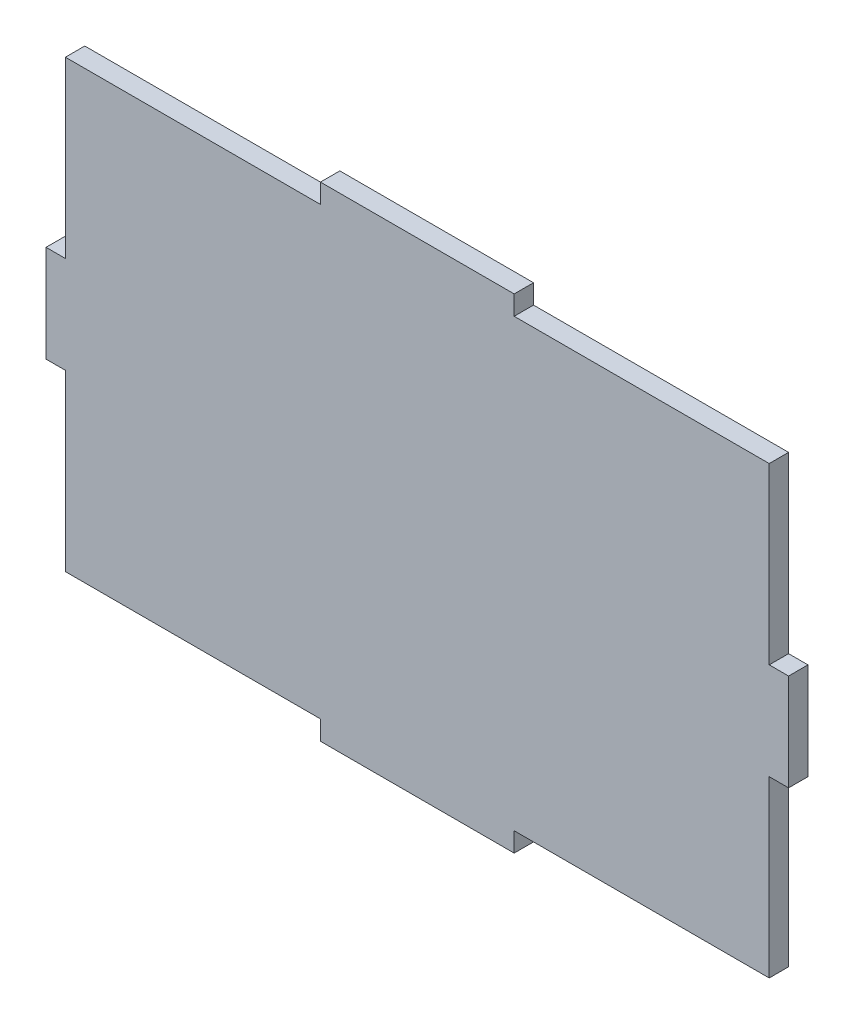
SolidWorks part; units mm, degrees
ref_plane "Front Plane" through (0, 0, 0) normal (0, 0, 1) x (1, 0, 0)
ref_plane "Top Plane" through (0, 0, 0) normal (0, 1, 0) x (1, 0, 0)
ref_plane "Right Plane" through (0, 0, 0) normal (1, 0, 0) x (0, 0, -1)
sketch "Sketch1" plane through (0, 0, 0) normal (0, 0, 1) x (1, 0, 0)
  line L0 (0, 45) -> (3, 45)
  line L1 (0, 0) -> (115, 0)
  line L2 (0, 0) -> (0, 75)
  line L3 (0, 75) -> (115, 75)
  line L4 (115, 0) -> (115, 75)
  line L5 (3, 45) -> (3, 72)
  line L6 (3, 72) -> (42.5, 72)
  line L7 (42.5, 72) -> (42.5, 75)
  line L8 (72.5, 75) -> (72.5, 72)
  line L9 (72.5, 72) -> (112, 72)
  line L10 (112, 72) -> (112, 45)
  line L11 (112, 45) -> (115, 45)
  line L12 (115, 30) -> (112, 30)
  line L13 (112, 30) -> (112, 3)
  line L14 (112, 3) -> (72.5, 3)
  line L15 (72.5, 3) -> (72.5, 0)
  line L16 (42.5, 0) -> (42.5, 3)
  line L17 (42.5, 3) -> (3, 3)
  line L18 (3, 3) -> (3, 30)
  line L19 (3, 30) -> (0, 30)
  line L20 (0, 37.5) -> (115, 37.5) construction
  line L21 (57.5, 75) -> (57.5, 0) construction
  point P29 (0, 0)
  point P30 (0, 0)
  point P31 (0, 0)
  point P32 (0, 0)
  point P33 (0, 0)
  point P34 (113.5, 45)
  point P36 (72.2946, 75)
  point P37 (0.6789, 31.646)
  dimension "D1" = 115
  dimension "D2" = 75
  dimension "D3" = 3
  dimension "D4" = 30
  dimension "D5" = 3
  dimension "D6" = 15
  dimension "D7" = 3
  dimension "D8" = 30
  dimension "D9" = 3
  dimension "D10" = 15
extrude "Boss-Extrude1" add sketch "Sketch1" along normal blind 3 contours L19 L18 L17 L16 L1 L15 L14 L13 L12 L4 L11 L10 L9 L8 L3 L7 L6 L5 L0 L2
